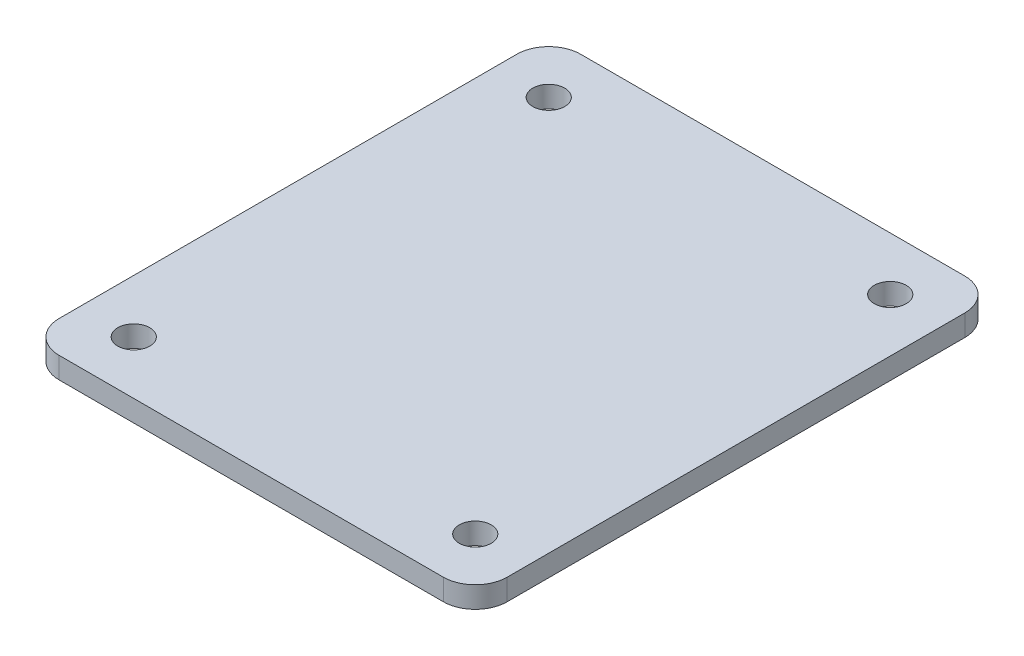
SolidWorks part; units mm, degrees
ref_plane "Спереди" through (0, 0, 0) normal (0, 0, 1) x (1, 0, 0)
ref_plane "Сверху" through (0, 0, 0) normal (0, 1, 0) x (1, 0, 0)
ref_plane "Справа" through (0, 0, 0) normal (1, 0, 0) x (0, 0, -1)
sketch "Эскиз1" plane through (0, 0, 0) normal (0, 1, 0) x (1, 0, 0)
  line L1 (-21.0194, -24.4666) -> (21.0194, -24.4666)
  line L2 (-21.0194, -24.4666) -> (-21.0194, 24.4666)
  line L3 (-21.0194, 24.4666) -> (21.0194, 24.4666)
  line L4 (21.0194, -24.4666) -> (21.0194, 24.4666)
  line L5 (-21.0194, -24.4666) -> (21.0194, 24.4666) construction
  line L6 (-21.0194, 24.4666) -> (21.0194, -24.4666) construction
  point P0 (0, 0)
extrude "Бобышка-Вытянуть1" add sketch "Эскиз1" along normal blind 2
sketch "Эскиз3" plane through (0, 2, 0) normal (0, 1, 0) x (1, 0, 0)
  line L8 (16.0194, -19.4666) -> (16.0194, 19.4666)
  line L9 (16.0194, 19.4666) -> (-16.0194, 19.4666)
  line L10 (-16.0194, 19.4666) -> (-16.0194, -19.4666)
  line L11 (-16.0194, -19.4666) -> (16.0194, -19.4666)
  line L12 (16.0194, -19.4666) -> (16.0194, 19.4666) construction
  line L13 (16.0194, 19.4666) -> (-16.0194, 19.4666) construction
  line L14 (-16.0194, 19.4666) -> (-16.0194, -19.4666) construction
  line L15 (-16.0194, -19.4666) -> (16.0194, -19.4666) construction
  circle A0 centre (-16.0194, 19.4666) radius 1.5
  circle A1 centre (16.0194, 19.4666) radius 1.5
  circle A2 centre (16.0194, -19.4666) radius 1.5
  circle A3 centre (-16.0194, -19.4666) radius 1.5
  dimension "D2" = 3
  dimension "D1" = 5
extrude "Вырез-Вытянуть1" cut sketch "Эскиз3" against normal through all
fillet "Скругление1" radius 3 4 edges at (-21.0194, 1, -24.4666) (21.0194, 1, -24.4666) (21.0194, 1, 24.4666) (-21.0194, 1, 24.4666)
